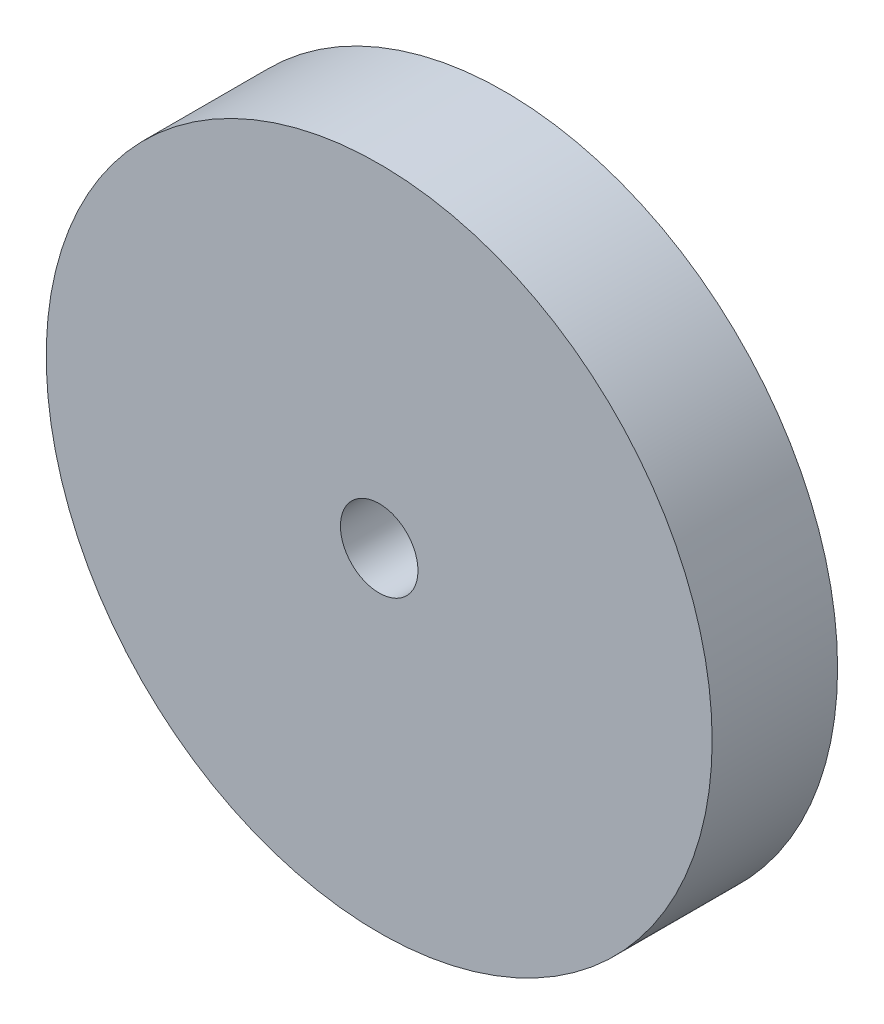
SolidWorks part; units mm, degrees
material "ABS"
ref_plane "Front Plane" through (0, 0, 0) normal (0, 0, 1) x (1, 0, 0)
ref_plane "Top Plane" through (0, 0, 0) normal (0, 1, 0) x (1, 0, 0)
ref_plane "Right Plane" through (0, 0, 0) normal (1, 0, 0) x (0, 0, -1)
sketch "Sketch1" plane through (0, 0, 0) normal (0, 0, 1) x (1, 0, 0)
  circle A0 centre (0, 0) radius 4.25
  circle A1 centre (0, 0) radius 36.5
  dimension "D1" = 8.5
  dimension "D2" = 73
extrude "Boss-Extrude1" add sketch "Sketch1" along normal blind 13.75
